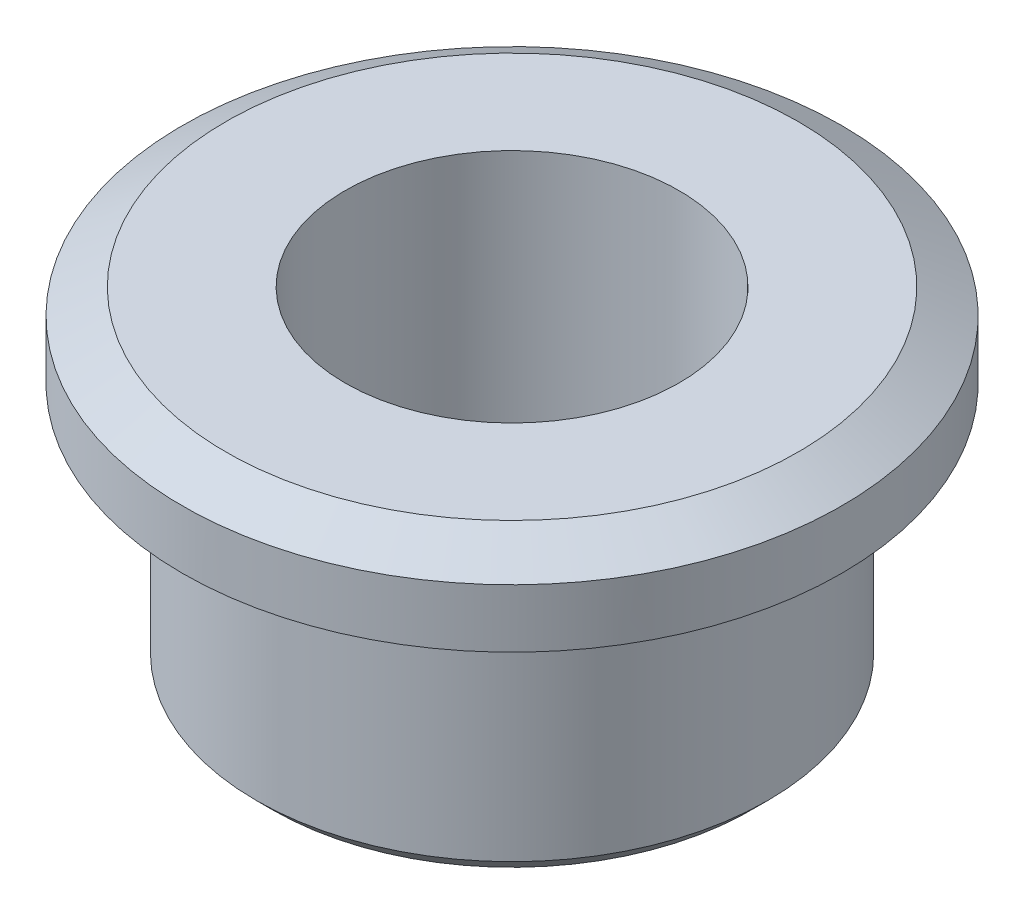
SolidWorks part; units mm, degrees
material "铸造碳钢"
ref_plane "前视基准面" through (0, 0, 0) normal (0, 0, 1) x (1, 0, 0)
ref_plane "上视基准面" through (0, 0, 0) normal (0, 1, 0) x (1, 0, 0)
ref_plane "右视基准面" through (0, 0, 0) normal (1, 0, 0) x (0, 0, -1)
sketch "草图1" plane through (0, 0, 0) normal (0, 1, 0) x (1, 0, 0)
  circle A0 centre (0, 0) radius 2
  circle A1 centre (0, 0) radius 3.065
  dimension "内径" = 4
  dimension "外径" = 6.13
extrude "凸台-拉伸1" add sketch "草图1" against normal blind 3
sketch "草图2" plane through (0, 0, 0) normal (0, 1, 0) x (1, 0, 0)
  circle A0 centre (0, 0) radius 2
  circle A1 centre (0, 0) radius 3.95
  circle A2 centre (0, 0) radius 2 construction
  dimension "翻边外径" = 7.9
extrude "凸台-拉伸2" add sketch "草图2" along normal blind 1
chamfer "倒角1" distance 0.3 angle 60 1 edges at (0, 1, 3.95)
chamfer "倒角2" distance 0.2 angle 45 1 edges at (0, -3, 3.065)
other "冻结***"
